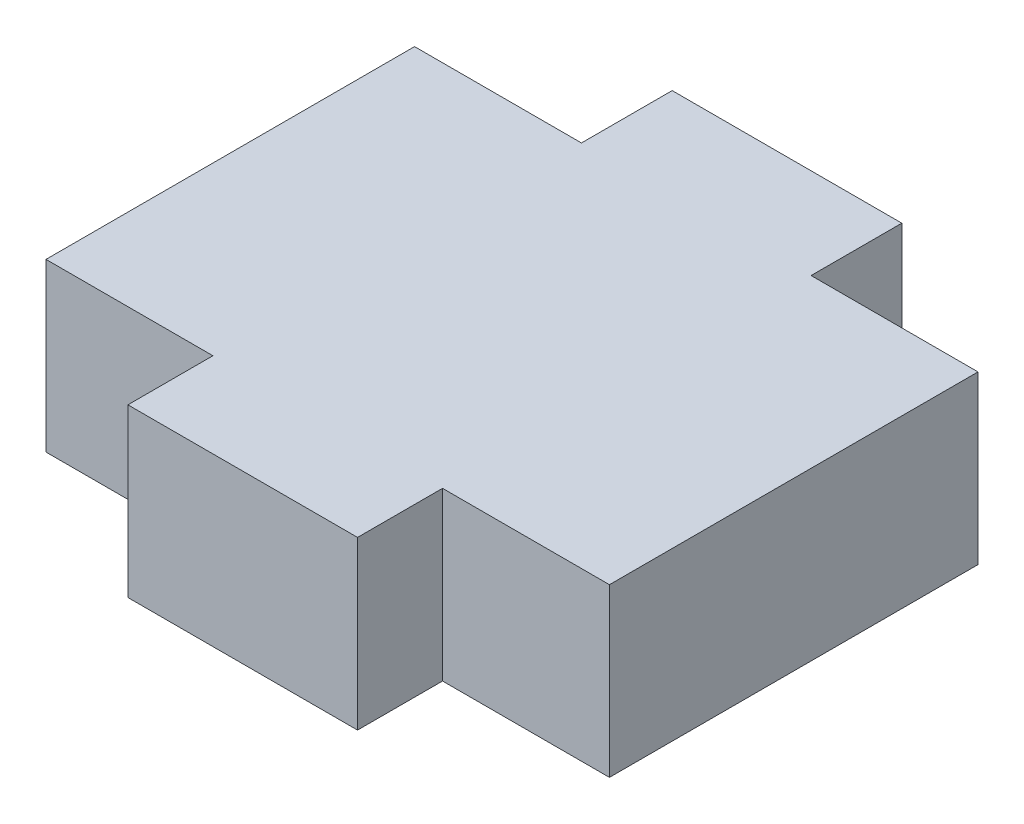
SolidWorks part; units mm, degrees
ref_plane "Front Plane" through (0, 0, 0) normal (0, 0, 1) x (1, 0, 0)
ref_plane "Top Plane" through (0, 0, 0) normal (0, 1, 0) x (1, 0, 0)
ref_plane "Right Plane" through (0, 0, 0) normal (1, 0, 0) x (0, 0, -1)
sketch "Sketch1" plane through (0, 0, 0) normal (0, 1, 0) x (1, 0, 0)
  line L0 (-4.0188, 19.05) -> (-4.0188, 0) construction
  line L1 (0, 0) -> (-8.0375, 0)
  line L2 (0, 0) -> (0, 2.975)
  line L3 (0, 19.05) -> (-8.0375, 19.05)
  line L4 (-8.0375, 0) -> (-8.0375, 2.975)
  line L5 (0, 2.975) -> (5.842, 2.975)
  line L6 (-13.8795, 2.975) -> (-13.8795, 15.875)
  line L7 (0, 15.875) -> (5.842, 15.875)
  line L8 (5.842, 2.975) -> (5.842, 15.875)
  line L9 (0, 15.875) -> (0, 19.05)
  line L10 (-8.0375, 15.875) -> (-13.8795, 15.875)
  line L11 (-8.0375, 2.975) -> (-13.8795, 2.975)
  line L12 (-8.0375, 15.875) -> (-8.0375, 19.05)
  dimension "D1" = 12.9
  dimension "D2" = 3.175
  dimension "D3" = 5.842
  dimension "D4" = 8.0375
  dimension "D5" = 19.05
extrude "Boss-Extrude1" add sketch "Sketch1" along normal blind 5.842
